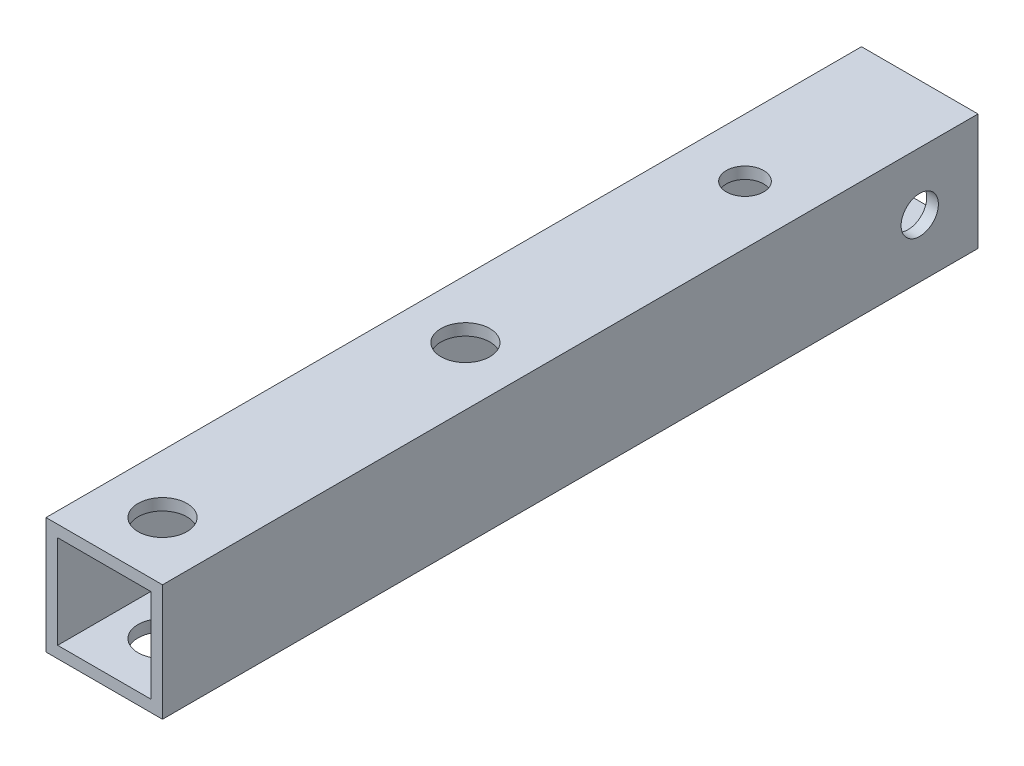
SolidWorks part; units mm, degrees
material "1060 合金"
ref_plane "正面" through (0, 0, 0) normal (0, 0, 1) x (1, 0, 0)
ref_plane "平面" through (0, 0, 0) normal (0, 1, 0) x (1, 0, 0)
ref_plane "右側面" through (0, 0, 0) normal (1, 0, 0) x (0, 0, -1)
sketch "ｽｹｯﾁ1" plane through (0, 0, 0) normal (0, 0, 1) x (1, 0, 0)
  line L1 (5, 5) -> (-5, 5)
  line L2 (5, 5) -> (5, -5)
  line L3 (5, -5) -> (-5, -5)
  line L4 (-5, 5) -> (-5, -5)
  line L5 (5, 5) -> (-5, -5) construction
  line L6 (5, -5) -> (-5, 5) construction
  point P0 (0, 0)
  dimension "D1" = 10
  dimension "D2" = 10
extrude "押し出し-薄板1" add sketch "ｽｹｯﾁ1" along normal blind 60 thin thin type one direction reverse wall 1
sketch "ｽｹｯﾁ3" plane through (0, 5, 0) normal (0, 1, 0) x (1, 0, 0)
  line L0 (0, 0) -> (0, -60) construction
  line L1 (5, -60) -> (-5, -60) construction
  line L2 (5, 0) -> (-5, 0) construction
  circle A0 centre (0, -55) radius 2.1
  circle A1 centre (0, -29) radius 2.1
  circle A2 centre (0, -5) radius 1.6
  dimension "D1" = 5
  dimension "D2" = 26
  dimension "D3" = 5
  dimension "D4" = 3.2
  dimension "D5" = 4.2
  dimension "D6" = 4.2
extrude "ｶｯﾄ - 押し出し1" cut sketch "ｽｹｯﾁ3" against normal through all
sketch "ｽｹｯﾁ7" plane through (0, 0, 0) normal (0, 0, -1) x (-1, 0, 0)
  line L1 (5, 5) -> (-5, 5)
  line L2 (5, 5) -> (5, -5)
  line L3 (5, -5) -> (-5, -5)
  line L4 (-5, 5) -> (-5, -5)
  line L5 (5, 5) -> (-5, -5) construction
  line L6 (5, -5) -> (-5, 5) construction
  line L7 (4, 4) -> (-4, 4)
  line L8 (4, 4) -> (4, -4)
  line L9 (4, -4) -> (-4, -4)
  line L10 (-4, 4) -> (-4, -4)
  line L11 (4, 4) -> (-4, -4) construction
  line L12 (4, -4) -> (-4, 4) construction
  point P0 (0, 0)
  point P7 (0, 0)
extrude "ﾎﾞｽ - 押し出し1" add sketch "ｽｹｯﾁ7" along normal blind 10
sketch "ｽｹｯﾁ8" plane through (-5, 0, 0) normal (-1, 0, 0) x (0, 0, 1)
  line L0 (-10, 0) -> (60, 0) construction
  line L1 (-10, -5) -> (-10, 5) construction
  line L2 (60, 5) -> (60, -5) construction
  circle A0 centre (-5, 0) radius 1.6
  dimension "D1" = 5
  dimension "D2" = 3.2
extrude "ｶｯﾄ - 押し出し5" cut sketch "ｽｹｯﾁ8" against normal through all
